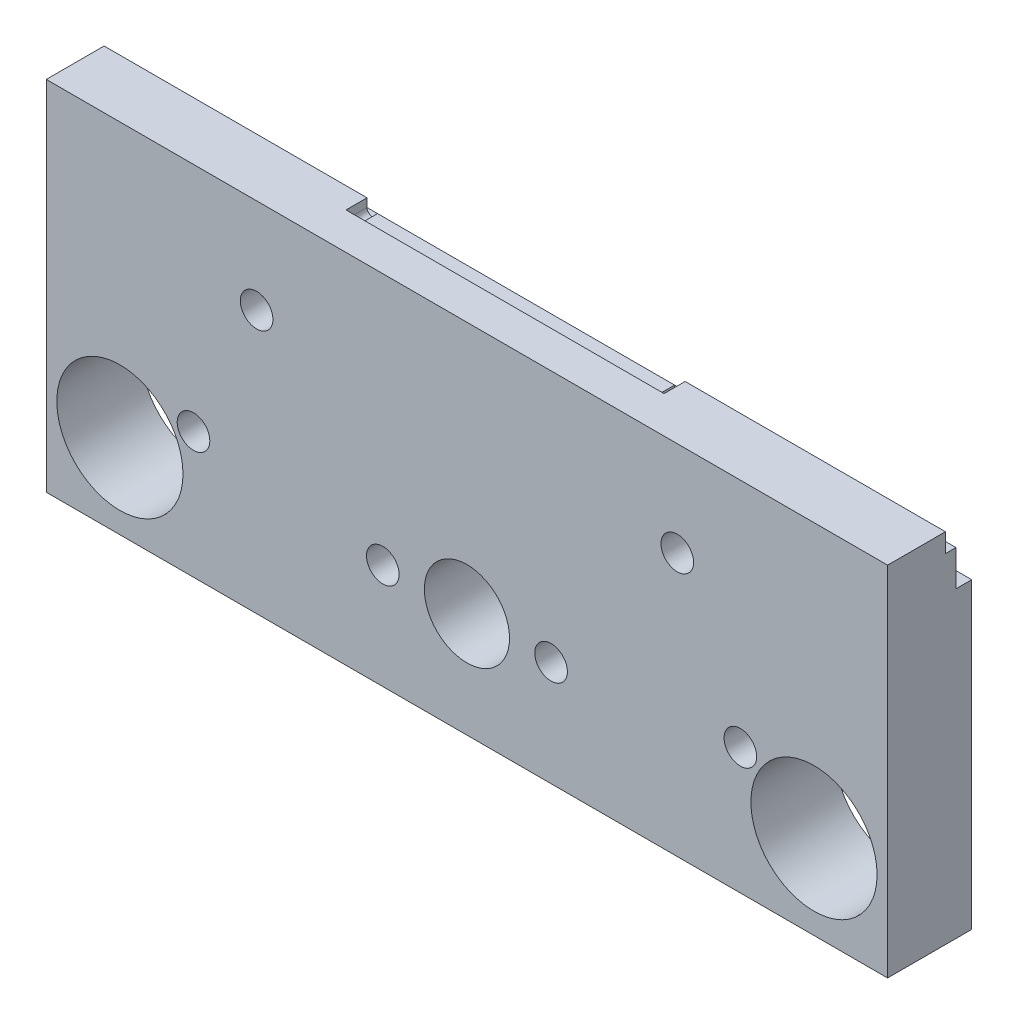
SolidWorks part; units mm, degrees
ref_plane "前视基准面" through (0, 0, 0) normal (0, 0, 1) x (1, 0, 0)
ref_plane "上视基准面" through (0, 0, 0) normal (0, 1, 0) x (1, 0, 0)
ref_plane "右视基准面" through (0, 0, 0) normal (1, 0, 0) x (0, 0, -1)
sketch "前视图草图" plane through (0, 0, 0) normal (0, 0, 1) x (1, 0, 0)
  line L0 (0, 0) -> (44.4821, 0) construction
  line L1 (0, 0) -> (0, 28.3185) construction
sketch "草图2" plane through (0, 0, 0) normal (0, 0, 1) x (1, 0, 0)
  line L0 (0, 0) -> (80, 0)
  line L1 (-200000, 0) -> (200044.4821, 0) construction
  line L2 (80, 0) -> (80, 34)
  line L3 (80, 34) -> (0, 34)
  line L4 (0, -200000) -> (0, 200028.3185) construction
  line L5 (0, 34) -> (0, 0)
  circle A0 centre (7, 8) radius 6
  circle A1 centre (40, 10) radius 4.05
  circle A2 centre (73, 8) radius 6
  dimension "D3" = 8
  dimension "D5" = 10
  dimension "D9" = 12
  dimension "D10" = 12
  dimension "D11" = 8.1
  dimension "D1" = 34
  dimension "D2" = 80
  dimension "D4" = 7
  dimension "D6" = 7
  dimension "D7" = 8
  dimension "D8" = 40
extrude "凸台-拉伸1" add sketch "草图2" along normal blind 8
sketch "草图3" plane through (0, 0, 8) normal (0, 0, 1) x (1, 0, 0)
  line L0 (16.088, 8) -> (31.4805, 8) construction
  line L1 (7, 8) -> (7, 16.8386) construction
  line L2 (73, 8) -> (73, 16.5917) construction
  line L4 (-200000, 0) -> (200044.4821, 0) construction
  circle A2 centre (23, 8) radius 2.55
  circle A3 centre (57, 8) radius 2.55
  dimension "D4" = 5.1
  dimension "D5" = 5.1
  dimension "D1" = 8
  dimension "D2" = 16
  dimension "D3" = 16
extrude "切除-拉伸1" [suppressed] cut sketch "草图3" against normal through all
sketch "草图4" plane through (80, 0, 0) normal (1, 0, 0) x (0, 0, -1)
  line L1 (0, -200000) -> (0, 200028.3185) construction
  line L2 (-1.5, 32.2) -> (-2.5, 32.2)
  line L3 (-2.5, 32.2) -> (-2.5, 34)
  line L4 (-8, 34) -> (0, 34) construction
  line L5 (-2.5, 34) -> (0, 34)
  line L6 (-1.5, 32.2) -> (-1.5, 28.8)
  line L7 (-1.5, 28.8) -> (0, 28.8)
  line L8 (0, 28.8) -> (0, 34)
  dimension "D1" = 3.4
  dimension "D2" = 2.5
  dimension "D3" = 1.5
  dimension "D4" = 1.8
extrude "切除-拉伸2" cut sketch "草图4" against normal through all
sketch "草图5" plane through (0, 0, 8) normal (0, 0, 1) x (1, 0, 0)
  line L0 (40, 10) -> (56.5376, 10) construction
  circle A0 centre (40, 10) radius 8 construction
  circle A1 centre (48, 10) radius 1.55
  circle A2 centre (32, 10) radius 1.55
  dimension "D1" = 3.1
  dimension "D2" = 3.1
  dimension "D3" = 16
extrude "切除-拉伸3" cut sketch "草图5" against normal through all
sketch "草图7" [suppressed] plane through (0, 0, 0) normal (0, 0, -1) x (-1, 0, 0)
  line L0 (-40, 12) -> (-40, -8.3696) construction
  line L1 (-23, 10) -> (-23, -2.3368) construction
  line L2 (200000, 0) -> (-200044.4821, 0) construction
  line L6 (-27.05, 10) -> (-27.05, 2.5)
  line L7 (-29.55, 0) -> (-16.45, 0)
  line L8 (-18.95, 2.5) -> (-18.95, 10)
  line L9 (-23, 8) -> (-23, 15.9045) construction
  line L13 (0, -200000) -> (0, 200028.3185) construction
  line L14 (-57, 8) -> (-57, 15.9045) construction
  line L15 (-57, 10) -> (-57, -2.3368) construction
  line L16 (-61.05, 2.5) -> (-61.05, 10)
  line L17 (-50.45, 0) -> (-63.55, 0)
  line L18 (-52.95, 10) -> (-52.95, 2.5)
  arc A1 (-18.95, 10) -> (-27.05, 10) centre (-23, 10) ccw
  arc A4 (-29.55, 0) -> (-27.05, 2.5) centre (-29.55, 2.5) ccw
  arc A5 (-18.95, 2.5) -> (-16.45, 0) centre (-16.45, 2.5) ccw
  arc A7 (-61.05, 2.5) -> (-63.55, 0) centre (-63.55, 2.5) cw
  arc A8 (-50.45, 0) -> (-52.95, 2.5) centre (-50.45, 2.5) cw
  arc A9 (-61.05, 10) -> (-52.95, 10) centre (-57, 10) cw
  dimension "D1" = 40
  dimension "D4" = 8.1
  dimension "D7" = 2.5
  dimension "D8" = 2.5
  dimension "D3" = 10
extrude "切除-拉伸4" [suppressed] cut sketch "草图7" against normal blind 6
sketch "草图8" plane through (0, 0, 0) normal (0, 0, -1) x (-1, 0, 0)
  line L0 (-40, 10) -> (-57.3165, 10) construction
  line L1 (-40, 20) -> (-40, 35.6562) construction
  line L2 (-30.5, 12.85) -> (-49.5, 12.85)
  line L3 (-49.5, 7.15) -> (-30.5, 7.15)
  line L4 (200000, 0) -> (-200044.4821, 0) construction
  line L5 (-80, 0) -> (-80, 28.8) construction
  line L6 (-45.15, 8.3546) -> (-45.15, 11.6454)
  line L7 (-45.15, 11.6454) -> (-48, 13.2909)
  line L8 (-48, 13.2909) -> (-50.85, 11.6454)
  line L9 (-50.85, 11.6454) -> (-50.85, 8.3546)
  line L10 (-50.85, 8.3546) -> (-48, 6.7091)
  line L11 (-48, 6.7091) -> (-45.15, 8.3546)
  line L12 (-34.85, 8.3546) -> (-32, 6.7091)
  line L13 (-32, 6.7091) -> (-29.15, 8.3546)
  line L14 (-29.15, 8.3546) -> (-29.15, 11.6454)
  line L15 (-29.15, 11.6454) -> (-32, 13.2909)
  line L16 (-32, 13.2909) -> (-34.85, 11.6454)
  line L17 (-34.85, 11.6454) -> (-34.85, 8.3546)
  arc A0 (-30.5, 7.15) -> (-30.5, 12.85) centre (-30.5, 10) ccw
  arc A1 (-49.5, 12.85) -> (-49.5, 7.15) centre (-49.5, 10) ccw
  circle A2 centre (-48, 10) radius 2.85 construction
  circle A3 centre (-32, 10) radius 2.85 construction
  dimension "D1" = 5.7
  dimension "D2" = 9.5
  dimension "D3" = 9.5
  dimension "D4" = 10
  dimension "D5" = 5.7
extrude "切除-拉伸5" cut sketch "草图8" against normal blind 4.5 contours L9 L10 L11 L6 L7 L8 | L17 L12 L13 L14 L15 L16
sketch "草图11" plane through (0, 0, 0) normal (0, 0, -1) x (-1, 0, 0)
  line L0 (0, 34) -> (-80, 34) construction
  line L1 (-80, 0) -> (-80, 28.8) construction
  line L2 (0, -200000) -> (0, 200028.3185) construction
  line L3 (-40, 20) -> (-40, 13.5744) construction
  line L4 (-28.772, 25) -> (-45.9396, 25) construction
  circle A0 centre (-60, 25) radius 1.55
  circle A1 centre (-20, 25) radius 1.55
  point P23 (-40, 20)
  dimension "D1" = 3.1
  dimension "D2" = 3.1
  dimension "D3" = 20
  dimension "D4" = 20
  dimension "D5" = 9
sketch "草图20" plane through (0, 0, 0) normal (0, 0, -1) x (-1, 0, 0)
  circle A0 centre (-40, 10) radius 5.5
  dimension "D1" = 11
extrude "切除-拉伸7" cut sketch "草图11" against normal through all contours A0 | A1
sketch "草图12" plane through (0, 0, 0) normal (0, 0, -1) x (-1, 0, 0)
  line L0 (-62.5, 22.15) -> (-57.5, 22.15)
  line L1 (-57.5, 27.85) -> (-62.5, 27.85)
  line L4 (-80, 0) -> (-80, 28.8) construction
  line L5 (-39.1423, 25) -> (-43.2672, 25) construction
  line L6 (-60, 21) -> (-60, 25.2385) construction
  line L7 (-20, 21) -> (-20, 26.1603) construction
  line L8 (-40, 20) -> (-40, 24.3689) construction
  line L9 (-17.5, 27.85) -> (-22.5, 27.85)
  line L10 (-22.5, 22.15) -> (-17.5, 22.15)
  line L11 (0, -200000) -> (0, 200028.3185) construction
  line L12 (0, 34) -> (-80, 34) construction
  arc A0 (-62.5, 27.85) -> (-62.5, 22.15) centre (-62.5, 25) ccw
  arc A1 (-57.5, 22.15) -> (-57.5, 27.85) centre (-57.5, 25) ccw
  arc A4 (-17.5, 22.15) -> (-17.5, 27.85) centre (-17.5, 25) ccw
  arc A5 (-22.5, 27.85) -> (-22.5, 22.15) centre (-22.5, 25) ccw
  point P16 (-38, 21)
  point P28 (-40, 25)
  dimension "D2" = 20
  dimension "D3" = 5
  dimension "D4" = 2.5
  dimension "D5" = 20
  dimension "D6" = 9
  dimension "D1" = 2
sketch "草图19" plane through (0, 0, 2.5) normal (0, 0, -1) x (-1, 0, 0)
  line L0 (0, 34) -> (-80, 34) construction
  line L1 (-25, 34) -> (-55.2479, 34)
  line L2 (-25, 34) -> (-25, 33.2)
  line L3 (-26, 33.2) -> (-54.2479, 33.2)
  line L4 (-55.2479, 34) -> (-55.2479, 33.2)
  line L5 (0, -200000) -> (0, 200028.3185) construction
  line L7 (0, 32.2) -> (-80, 32.2) construction
  line L8 (-56.3335, 32.7) -> (-52.9089, 32.7) construction
  line L9 (-55.2479, 1028.5823) -> (-55.2479, 33.2) construction
  line L10 (-25, 1028.5823) -> (-25, 32.7) construction
  line L11 (-55.2479, 32.7) -> (-55.2479, -973.3) construction
  line L12 (-25, 32.7) -> (-25, -973.3) construction
  arc A3 (-55.2479, 33.2) -> (-54.2479, 33.2) centre (-54.7479, 33.2) ccw
  arc A6 (-26, 33.2) -> (-25, 33.2) centre (-25.5, 33.2) ccw
  dimension "D3" = 1
  dimension "D4" = 1
  dimension "D2" = 0.8
  dimension "D1" = 0.5
  dimension "D9" = 25
extrude "切除-拉伸11" cut sketch "草图19" against normal blind 2
sketch "草图22" plane through (0, 0, 0) normal (0, 0, -1) x (-1, 0, 0)
  line L0 (-66, 0) -> (-66, 28.8) construction
  line L1 (200000, 0) -> (-200044.4821, 0) construction
  line L2 (0, 28.8) -> (-80, 28.8) construction
  line L3 (-80, 12) -> (0, 12) construction
  line L4 (-80, 0) -> (-80, 28.8) construction
  line L5 (0, -200000) -> (0, 200028.3185) construction
  line L7 (-40, 32.2) -> (-40, 0) construction
  line L8 (0, 32.2) -> (-80, 32.2) construction
  line L10 (-40, -199980) -> (-40, 200024.3689) construction
  circle A0 centre (-66, 12) radius 1.55
  circle A1 centre (-14, 12) radius 1.55
  dimension "D3" = 3.1
  dimension "D1" = 12
  dimension "D2" = 14
extrude "切除-拉伸13" cut sketch "草图22" against normal through all
